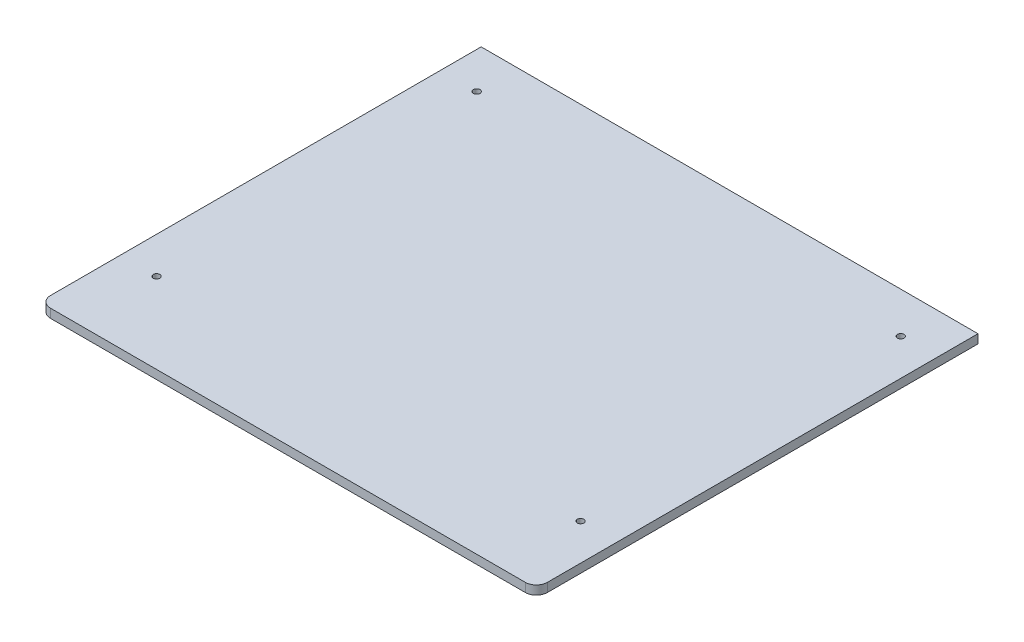
SolidWorks part; units mm, degrees
material "Glass"
ref_plane "Front Plane" through (0, 0, 0) normal (0, 0, 1) x (1, 0, 0)
ref_plane "Top Plane" through (0, 0, 0) normal (0, 1, 0) x (1, 0, 0)
ref_plane "Right Plane" through (0, 0, 0) normal (1, 0, 0) x (0, 0, -1)
sketch "Sketch1" plane through (0, 0, 0) normal (0, 1, 0) x (1, 0, 0)
  line L1 (0, 0) -> (450, 0)
  line L2 (0, 0) -> (0, -400)
  line L3 (0, -400) -> (450, -400)
  line L4 (450, 0) -> (450, -400)
  dimension "D1" = 450
  dimension "D2" = 400
extrude "Extrude1" add sketch "Sketch1" along normal blind 8
sketch "Sketch2" plane through (0, 8, 0) normal (0, 1, 0) x (-1, 0, 0)
  line L0 (-450, 0) -> (0, 0) construction
  line L1 (0, 0) -> (0, 400) construction
  circle A0 centre (-33, 37) radius 3
  circle A1 centre (-33, 327) radius 3
  circle A2 centre (-417, 37) radius 3
  circle A3 centre (-417, 327) radius 3
  dimension "D1" = 6
  dimension "D2" = 6
  dimension "D6" = 6
  dimension "D7" = 6
  dimension "D3" = 290
  dimension "D4" = 37
  dimension "D5" = 33
  dimension "D8" = 384
extrude "Extrude2" cut sketch "Sketch2" against normal through all
fillet "Fillet1" radius 10 2 edges at (450, 4, 400) (0, 4, 400)
